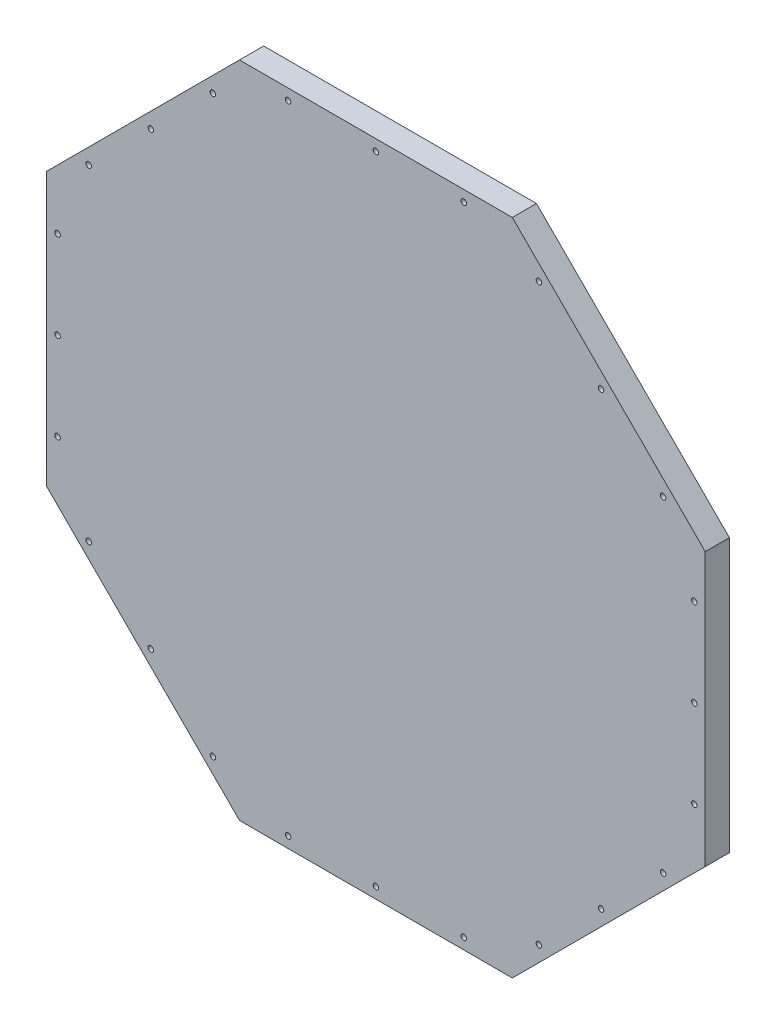
SolidWorks part; units mm, degrees
ref_plane "정면" through (0, 0, 0) normal (0, 0, 1) x (1, 0, 0)
ref_plane "윗면" through (0, 0, 0) normal (0, 1, 0) x (1, 0, 0)
ref_plane "우측면" through (0, 0, 0) normal (1, 0, 0) x (0, 0, -1)
sketch "스케치1" plane through (0, 0, 0) normal (0, 0, 1) x (1, 0, 0)
  line L0 (-368.8856, 0) -> (405.5856, 0) construction
  line L1 (124.2641, 300) -> (-124.2641, 300)
  line L2 (-124.2641, 300) -> (-300, 124.2641)
  line L3 (-300, 124.2641) -> (-300, -124.2641)
  line L4 (-300, -124.2641) -> (-124.2641, -300)
  line L5 (-124.2641, -300) -> (124.2641, -300)
  line L6 (124.2641, -300) -> (300, -124.2641)
  line L7 (300, -124.2641) -> (300, 124.2641)
  line L8 (300, 124.2641) -> (124.2641, 300)
  line L9 (-117.1614, 290) -> (111.2666, 290) construction
  line L10 (0, 353.0445) -> (0, -373.7324) construction
  line L11 (-300, -300) -> (300, 300) construction
  line L12 (-300, 300) -> (300, -300) construction
  circle A0 centre (0, 0) radius 300 construction
  circle A1 centre (0, 290) radius 2.5
  circle A2 centre (80, 290) radius 2.5
  circle A3 centre (-80, 290) radius 2.5
  circle A4 centre (148.4924, 261.6295) radius 2.5
  circle A5 centre (205.061, 205.061) radius 2.5
  circle A6 centre (261.6295, 148.4924) radius 2.5
  circle A7 centre (290, 80) radius 2.5
  circle A8 centre (290, 0) radius 2.5
  circle A9 centre (290, -80) radius 2.5
  circle A10 centre (261.6295, -148.4924) radius 2.5
  circle A11 centre (205.061, -205.061) radius 2.5
  circle A12 centre (148.4924, -261.6295) radius 2.5
  circle A13 centre (80, -290) radius 2.5
  circle A14 centre (0, -290) radius 2.5
  circle A15 centre (-80, -290) radius 2.5
  circle A16 centre (-148.4924, -261.6295) radius 2.5
  circle A17 centre (-205.061, -205.061) radius 2.5
  circle A18 centre (-261.6295, -148.4924) radius 2.5
  circle A19 centre (-290, -80) radius 2.5
  circle A20 centre (-290, 0) radius 2.5
  circle A21 centre (-290, 80) radius 2.5
  circle A22 centre (-261.6295, 148.4924) radius 2.5
  circle A23 centre (-205.061, 205.061) radius 2.5
  circle A24 centre (-148.4924, 261.6295) radius 2.5
  point P25 (0, 0)
  point P68 (0, 0)
  dimension "D2" = 5
  dimension "D3" = 10
  dimension "D4" = 80
  dimension "D5" = 80
  dimension "D7" = 45
  dimension "D1" = 600
  dimension "D8" = 45
  dimension "D6" = 8
extrude "보스-돌출1" add sketch "스케치1" along normal blind 22
